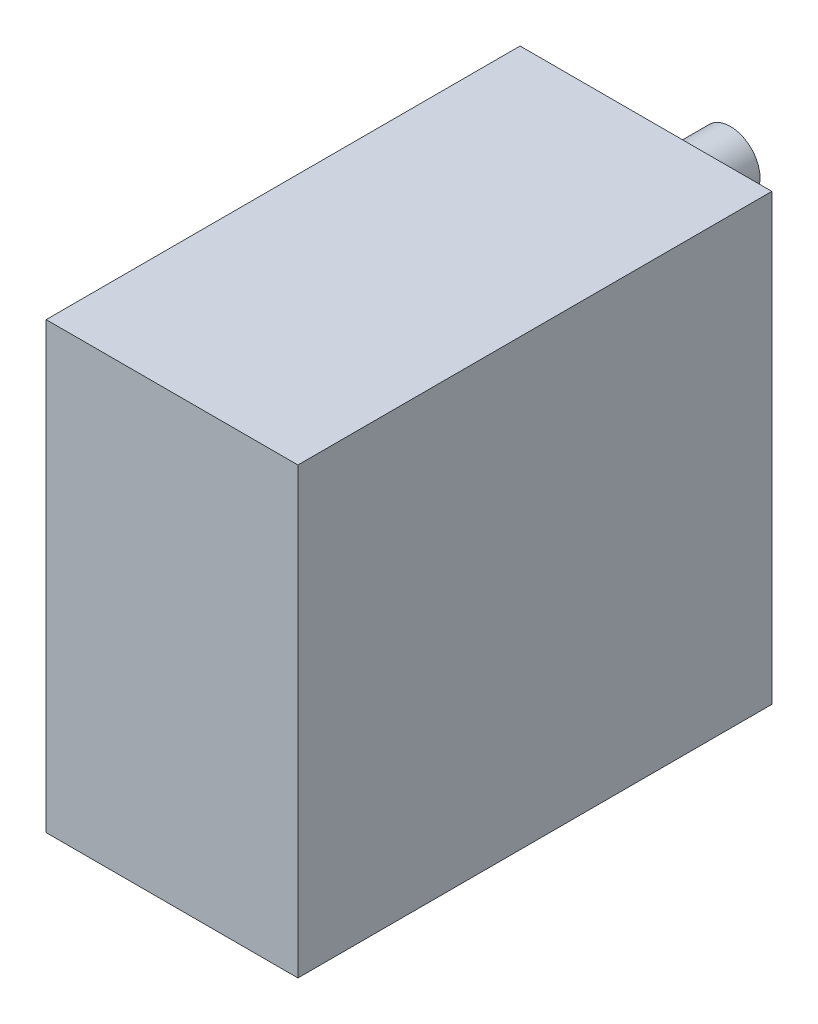
SolidWorks part; units mm, degrees
ref_plane "Front Plane" through (0, 0, 0) normal (0, 0, 1) x (1, 0, 0)
ref_plane "Top Plane" through (0, 0, 0) normal (0, 1, 0) x (1, 0, 0)
ref_plane "Right Plane" through (0, 0, 0) normal (1, 0, 0) x (0, 0, -1)
sketch "Sketch3" plane through (0, 0, 0) normal (0, 1, 0) x (1, 0, 0)
  line L0 (-144.6153, -125.1793) -> (25.3847, -125.1793)
  line L1 (-144.6153, -125.1793) -> (-144.6153, 194.8207)
  line L2 (-144.6153, 194.8207) -> (25.3847, 194.8207)
  line L3 (25.3847, -125.1793) -> (25.3847, 194.8207)
  line L4 (-144.6153, -125.1793) -> (25.3847, 194.8207) construction
  line L5 (-144.6153, 194.8207) -> (25.3847, -125.1793) construction
  point P0 (-59.6153, 34.8207)
  dimension "D1" = 320
  dimension "D2" = 170
extrude "Boss-Extrude2" add sketch "Sketch3" along normal blind 300
sketch "Sketch4" plane through (0, 0, 125.1793) normal (0, 0, 1) x (1, 0, 0)
  line L0 (-144.6153, 300) -> (25.3847, 300)
  line L1 (-144.6153, 247) -> (25.3847, 247)
  circle A0 centre (-59.6153, 247) radius 15
  circle A1 centre (-59.6153, 247) radius 20
  dimension "D2" = 5
  dimension "D1" = 53
sketch "Sketch6" plane through (0, 0, -194.8207) normal (0, 0, -1) x (-1, 0, 0)
  line L0 (-25.3847, 300) -> (144.6153, 300)
  line L1 (-25.3847, 247) -> (144.6153, 247)
  circle A0 centre (59.6153, 247) radius 15
  circle A1 centre (59.6153, 247) radius 20
  point P8 (0, 0)
  point P9 (0, 0)
  point P10 (0, 0)
  point P12 (0, 0)
  point P14 (0, 0)
  point P15 (0, 0)
extrude "Boss-Extrude4" add sketch "Sketch6" along normal blind 57 contours L1 A0 | L1 A0 | A1
